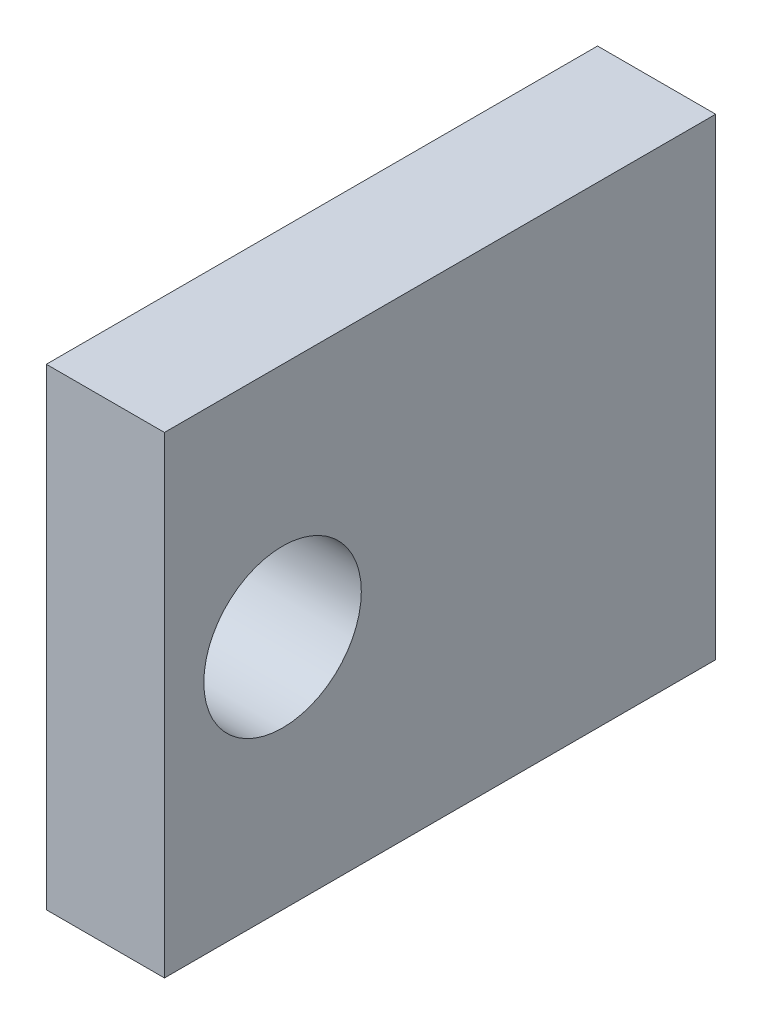
SolidWorks part; units mm, degrees
material "AISI 1020"
ref_plane "Front Plane" through (0, 0, 0) normal (0, 0, 1) x (1, 0, 0)
ref_plane "Top Plane" through (0, 0, 0) normal (0, 1, 0) x (1, 0, 0)
ref_plane "Right Plane" through (0, 0, 0) normal (1, 0, 0) x (0, 0, -1)
sketch "Sketch1" plane through (0, 0, 0) normal (1, 0, 0) x (0, 0, -1)
  line L1 (-22.225, -19.05) -> (22.225, -19.05)
  line L2 (-22.225, -19.05) -> (-22.225, 19.05)
  line L3 (-22.225, 19.05) -> (22.225, 19.05)
  line L4 (22.225, -19.05) -> (22.225, 19.05)
  line L5 (-22.225, -19.05) -> (22.225, 19.05) construction
  line L6 (-22.225, 19.05) -> (22.225, -19.05) construction
  circle A0 centre (-12.7, 0) radius 6.35
  point P0 (0, 0)
  dimension "D3" = 12.7
  dimension "D4" = 9.525
  dimension "D1" = 44.45
  dimension "D2" = 38.1
extrude "Boss-Extrude1" add sketch "Sketch1" along normal blind 9.525
